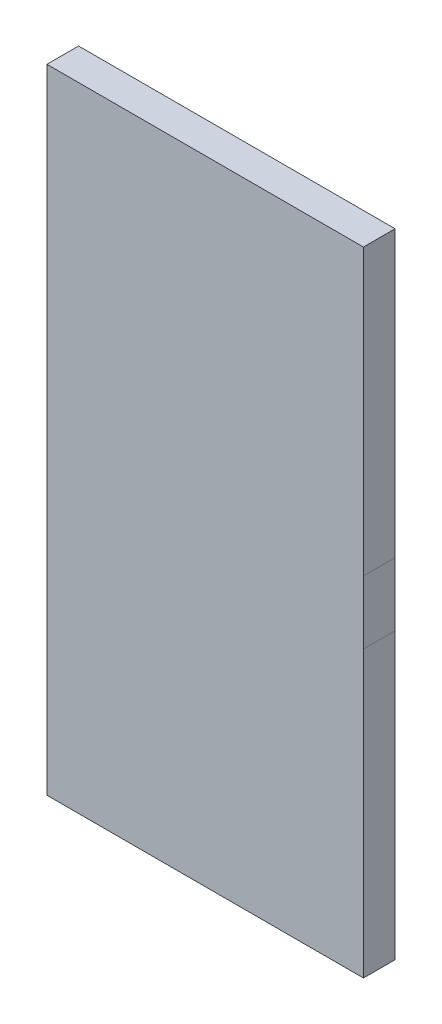
SolidWorks part; units mm, degrees
ref_plane "Front Plane" through (0, 0, 0) normal (0, 0, 1) x (1, 0, 0)
ref_plane "Top Plane" through (0, 0, 0) normal (0, 1, 0) x (1, 0, 0)
ref_plane "Right Plane" through (0, 0, 0) normal (1, 0, 0) x (0, 0, -1)
sketch "Sketch1" plane through (0, 0, 0) normal (0, 0, 1) x (1, 0, 0)
  line L1 (0, 0) -> (1000, 0)
  line L2 (0, 0) -> (0, 2000)
  line L3 (0, 2000) -> (1000, 2000)
  line L4 (1000, 0) -> (1000, 2000)
  dimension "D1" = 1000
  dimension "D2" = 2000
extrude "Boss-Extrude1" add sketch "Sketch1" along normal blind 100
sketch "Sketch2" plane through (1000, 0, 0) normal (1, 0, 0) x (0, 0, -1)
  line L0 (-100, 900) -> (0, 900)
  line L1 (-100, 0) -> (-100, 2000) construction
  line L2 (0, 0) -> (0, 2000) construction
  line L3 (-100, 1100) -> (0, 1100)
  line L4 (-100, 0) -> (0, 0) construction
  dimension "D1" = 200
  dimension "D2" = 900
split line "Split Line1"
